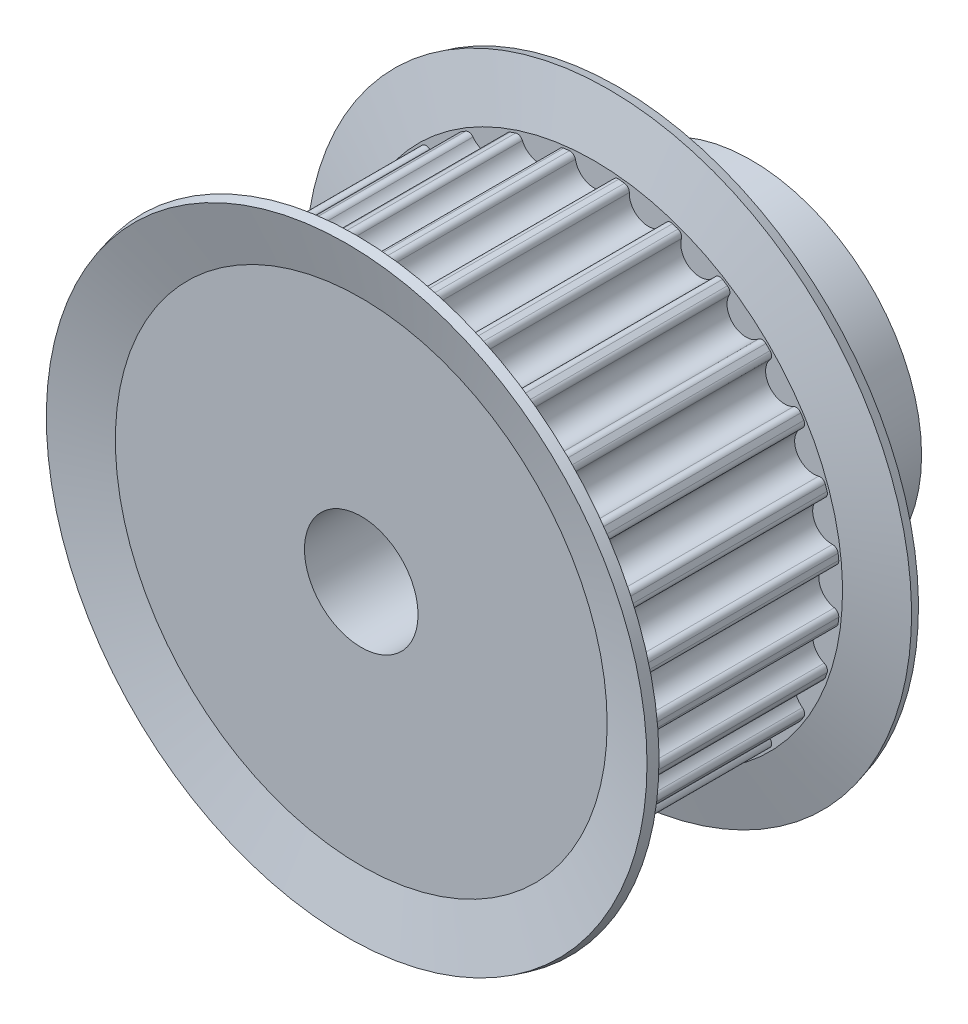
SolidWorks part; units mm, degrees
ref_plane "Front" through (0, 0, 0) normal (0, 0, 1) x (1, 0, 0)
ref_plane "Top" through (0, 0, 0) normal (0, 1, 0) x (1, 0, 0)
ref_plane "Right" through (0, 0, 0) normal (1, 0, 0) x (0, 0, -1)
sketch "Ritning 1" plane through (0, 0, 0) normal (1, 0, 0) x (0, 0, -1)
  line L0 (6.4, 6.495) -> (6.4, 2.505)
  line L1 (-6.4, 6.495) -> (6.4, 6.495)
  line L2 (-6.4, 6.495) -> (-6.4, -6.495)
  line L3 (-6.4, -6.495) -> (6.4, -6.495) construction
  line L4 (-6.4, -6.495) -> (6.4, -6.495)
  line L5 (14.2, 2.505) -> (14.2, -6.495)
  line L6 (6.4, 2.505) -> (14.2, 2.505)
  line L7 (14.2, -6.495) -> (6.4, -6.495) construction
  line L9 (14.2, -6.495) -> (6.4, -6.495)
  dimension "D1" = 6.4
  dimension "D2" = 14.2
  dimension "D3" = 6.4
  dimension "D4" = 2.505
  dimension "D5" = 6.495
  dimension "D6" = 6.495
revolve "Kugghjulsämne" add sketch "Ritning 1" angle 360 about L4
sketch "Ritning 2" plane through (0, 0, 6.4) normal (0, 0, 1) x (1, 0, 0)
  line L0 (0, 5.375) -> (0, -6.495) construction
  line L1 (1.3025, 6.4295) -> (1.3025, 7.5495)
  line L2 (1.3025, 7.5495) -> (-1.3025, 7.5495)
  line L3 (-1.3025, 7.5495) -> (-1.3025, 6.4295)
  arc A0 (1.3025, 6.4295) -> (0.9887, 6.1948) centre (1.2735, 6.1412) ccw
  arc A1 (-0.9887, 6.1948) -> (-1.3025, 6.4295) centre (-1.2735, 6.1412) ccw
  arc A2 (-0.9887, 6.1948) -> (0.9887, 6.1948) centre (0, 6.381) ccw
  circle A3 centre (0, -6.495) radius 12.99 construction
  dimension "D1" = 0.2898
  dimension "D2" = 1.006
  dimension "D3" = 0.9887
  dimension "D4" = 1.3025
  dimension "D5" = 12.6362
  dimension "D6" = 14.0445
extrude "Kugglucka" cut sketch "Ritning 2" against normal up to surface (12.8 mm away) up to face at (12.99, -6.495, -6.4)
pattern_circular "CirPattern" count 28 over 360 about axis through (0, -6.495, 0) along (0, 0, 1) of "Kugglucka"
sketch "Ritning 3" plane through (0, 0, 0) normal (1, 0, 0) x (0, 0, -1)
  line L1 (-5.9, 4.7815) -> (-6.4, 4.7815)
  line L2 (-5.9, 6.629) -> (-5.9, 4.7815)
  line L3 (-7.1706, 9.371) -> (-6.6706, 9.505)
  line L4 (-6.4, 6.495) -> (-7.1706, 9.371)
  line L5 (-6.4, 4.7815) -> (-6.4, 6.495)
  line L6 (-5.9, 6.629) -> (-6.6706, 9.505)
  line L7 (6.4, -6.495) -> (-6.4, -6.495) construction
  line L9 (5.9, 4.7815) -> (6.4, 4.7815)
  line L10 (5.9, 6.629) -> (5.9, 4.7815)
  line L11 (7.1706, 9.371) -> (6.6706, 9.505)
  line L12 (6.4, 6.495) -> (7.1706, 9.371)
  line L13 (6.4, 4.7815) -> (6.4, 6.495)
  line L14 (5.9, 6.629) -> (6.6706, 9.505)
  dimension "D1" = 5.9
  dimension "D2" = 6.4
  dimension "D3" = 6.6706
  dimension "D4" = 7.1706
  dimension "D5" = 5.9
  dimension "D6" = 6.4
  dimension "D7" = 6.6706
  dimension "D8" = 7.1706
  dimension "D9" = 4.7815
  dimension "D10" = 6.495
  dimension "D11" = 6.629
  dimension "D12" = 9.371
  dimension "D13" = 9.505
  dimension "D14" = 6.495
revolve "Flänsar" add sketch "Ritning 3" angle 360 about L7
sketch "Ritning 4" plane through (0, 0, 6.4) normal (0, 0, 1) x (1, 0, 0)
  circle A0 centre (0, -6.495) radius 3
  dimension "D1" = 6
extrude "Axelhål" cut sketch "Ritning 4" against normal through all
